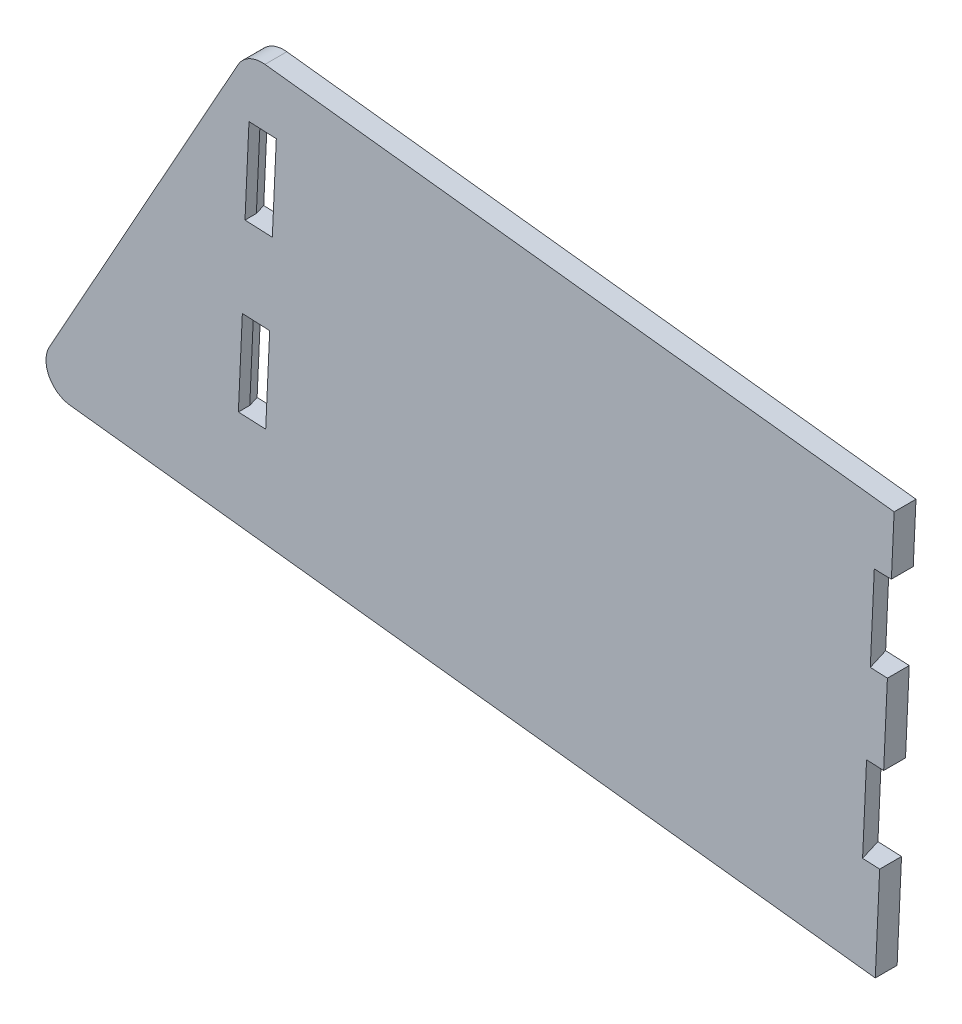
SolidWorks part; units mm, degrees
material "AISI 4340 Aço recozido"
ref_plane "Plano frontal" through (0, 0, 0) normal (0, 0, 1) x (1, 0, 0)
ref_plane "Plano superior" through (0, 0, 0) normal (0, 1, 0) x (1, 0, 0)
ref_plane "Plano direito" through (0, 0, 0) normal (1, 0, 0) x (0, 0, -1)
sketch "Esboço1" plane through (0, 0, 0) normal (0, 0, 1) x (1, 0, 0)
  line L0 (0, 0) -> (0, 76)
  line L1 (0, 76) -> (118.4502, 62.2675)
  line L3 (115, -13.3325) -> (0, 0)
  line L4 (118.4502, 62.2675) -> (115, -13.3325)
  dimension "D1" = 75.6
  dimension "D2" = 115
  dimension "D4" = 76
  dimension "D5" = 86
extrude "Ressalto-extrusão1" add sketch "Esboço1" along normal blind 4
sketch "Esboço13" plane through (0, 0, 4) normal (0, 0, 1) x (1, 0, 0)
  line L0 (0, 0) -> (-39.7569, 4.6092)
  line L1 (-39.7569, 4.6092) -> (0, 76)
  line L2 (0, 76) -> (0, 0)
  line L3 (0, 0) -> (115, -13.3325) construction
  dimension "D2" = 67.5
extrude "Ressalto-extrusão5" add sketch "Esboço13" against normal blind 4
ref_plane "Plano3" through (10.5333, -0.4807, 35.325) normal (0.2857, -0.013, 0.9582) x (0.0456, 0.999, 0)
sketch "Esboço15" plane through (10.5333, -0.4807, 35.325) normal (0.2857, -0.013, 0.9582) x (0.0456, 0.999, 0)
  line L0 (49.0471, 3.0145) -> (65.0471, 3.0145)
  line L1 (65.0471, 3.0145) -> (65.0471, -1.1855)
  line L2 (65.0471, -1.1855) -> (49.0471, -1.1855)
  line L3 (49.0471, -1.1855) -> (49.0471, 3.0145)
  line L4 (18.0017, 2.8196) -> (34.0017, 2.8196)
  line L5 (34.0017, 2.8196) -> (34.0017, -1.3804)
  line L6 (34.0017, -1.3804) -> (18.0017, -1.3804)
  line L7 (18.0017, -1.3804) -> (18.0017, 2.8196)
  line L8 (56.603, -109.5194) -> (56.603, -106.5194)
  line L10 (75.921, 4.4642) -> (2.7919, 39.4018) construction
  line L11 (56.603, -106.5194) -> (40.603, -106.5194)
  line L12 (67.603, -109.5194) -> (75.921, 4.4642) construction
  line L13 (40.603, -106.5194) -> (40.603, -109.5194)
  line L14 (40.603, -109.5194) -> (56.603, -109.5194)
  line L15 (9.603, -109.5194) -> (9.603, -106.5194)
  line L17 (9.603, -106.5194) -> (25.603, -106.5194)
  line L18 (25.603, -106.5194) -> (25.603, -109.5194)
  line L19 (25.603, -109.5194) -> (9.603, -109.5194)
  line L20 (-8.0757, -109.5194) -> (67.603, -109.5194) construction
  dimension "D1" = 4.2
  dimension "D2" = 4.2
  dimension "D3" = 16
  dimension "D4" = 16
  dimension "D5" = 19.5546
  dimension "D6" = 5.9956
  dimension "D7" = 10.4339
  dimension "D8" = 41.3827
  dimension "D9" = 3
  dimension "D10" = 16
  dimension "D11" = 16
  dimension "D12" = 11
  dimension "D13" = 42
extrude "Corte-extrusão2" cut sketch "Esboço15" against normal through all
sketch "Esboço16" plane through (0, 0, 4) normal (0, 0, 1) x (1, 0, 0)
  line L0 (116.385, 51.3503) -> (121.3954, 51.3503)
  line L1 (117.9487, 51.279) -> (114.8212, 51.4217) construction
  line L2 (121.3954, 51.3503) -> (120.6555, 35.1388)
  line L3 (120.6555, 35.1388) -> (115.6555, 35.367)
  line L4 (114.0917, 35.4383) -> (117.2193, 35.2956) construction
  line L5 (115.6555, 35.367) -> (116.385, 51.3503)
  line L6 (114.9717, 20.3826) -> (118.9717, 20.2)
  line L7 (116.5354, 20.3112) -> (113.4079, 20.4539) construction
  line L8 (118.9717, 20.2) -> (118.2422, 4.2166)
  line L9 (118.2422, 4.2166) -> (114.2422, 4.3992)
  line L10 (112.6784, 4.4706) -> (115.806, 4.3278) construction
  line L11 (114.2422, 4.3992) -> (114.9717, 20.3826)
  dimension "D1" = 5
  dimension "D2" = 4
extrude "Corte-extrusão3" cut sketch "Esboço16" against normal through all
fillet "Filete1" radius 5 2 edges at (0, 76, 2) (-39.7569, 4.6092, 2)
sketch "Esboço17" plane through (0, 0, 4) normal (0, 0, 1) x (1, 0, 0)
  line L0 (118.4502, 62.2675) -> (127.3903, 61.231)
  line L1 (127.3903, 61.231) -> (125.5042, 19.9019)
  line L2 (125.5042, 19.9019) -> (116.5354, 20.3112)
  line L3 (116.5354, 20.3112) -> (117.2193, 35.2956)
  line L4 (117.2193, 35.2956) -> (118.7162, 35.2273)
  line L5 (118.7162, 35.2273) -> (119.452, 51.3503)
  line L6 (119.452, 51.3503) -> (117.952, 51.3503)
  line L7 (117.952, 51.3503) -> (118.4502, 62.2675)
  line L8 (118.4502, 62.2675) -> (3.3187, 75.6153) construction
  line L9 (116.5354, 20.3112) -> (113.4079, 20.4539) construction
  line L10 (117.952, 51.3503) -> (116.385, 51.3503) construction
  line L11 (114.0917, 35.4383) -> (117.2193, 35.2956) construction
  dimension "D1" = 9
  dimension "D2" = 1.5
extrude "Ressalto-extrusão6" [suppressed] add sketch "Esboço17" against normal blind 4
sketch "Esboço19" plane through (0, 0, 4) normal (0, 0, 1) x (1, 0, 0)
  line L0 (5.3941, 64.8686) -> (0.3941, 65.0968)
  line L1 (0.3941, 65.0968) -> (-0.3353, 49.1134)
  line L2 (-0.3353, 49.1134) -> (4.6647, 48.8853)
  line L3 (4.6647, 48.8853) -> (5.3941, 64.8686)
  line L4 (4.182, 33.8462) -> (3.4525, 17.8629)
  line L5 (3.4525, 17.8629) -> (-1.5475, 18.091)
  line L6 (-1.5475, 18.091) -> (-0.818, 34.0744)
  line L7 (-0.818, 34.0744) -> (4.182, 33.8462)
  dimension "D1" = 5
  dimension "D2" = 5
extrude "Corte-extrusão4" cut sketch "Esboço19" against normal through all
